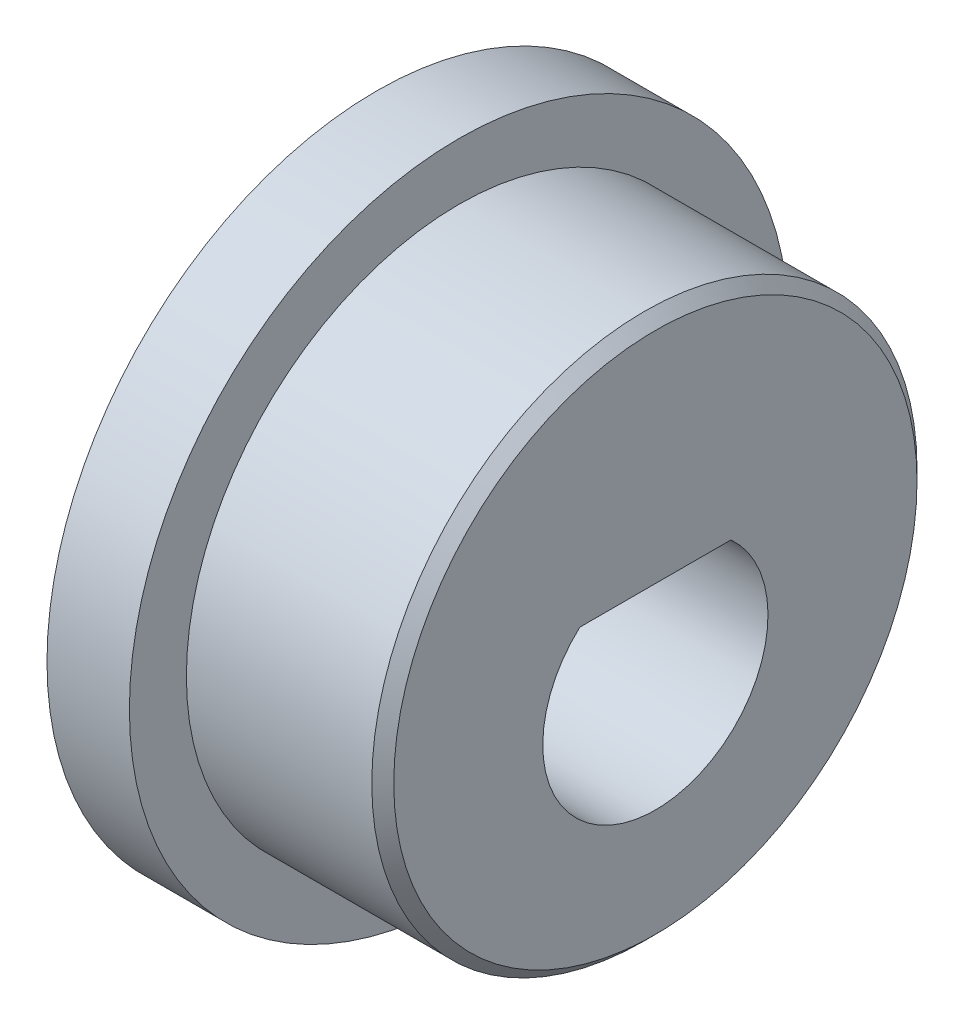
SolidWorks part; units mm, degrees
ref_plane "Ebene vorne" through (0, 0, 0) normal (0, 0, 1) x (1, 0, 0)
ref_plane "Ebene oben" through (0, 0, 0) normal (0, 1, 0) x (1, 0, 0)
ref_plane "Ebene rechts" through (0, 0, 0) normal (1, 0, 0) x (0, 0, -1)
sketch "Skizze1" plane through (0, 0, 0) normal (1, 0, 0) x (0, 0, -1)
  circle A0 centre (0, 1.5) radius 9.925
  dimension "D2" = 19.85
  dimension "D1" = 1.5
extrude "Aufsatz-Linear austragen1" add sketch "Skizze1" along normal blind 7.15
sketch "Skizze2" plane through (0, 0, 0) normal (-1, 0, 0) x (0, 0, 1)
  circle A0 centre (0, 1.5) radius 12
  dimension "D1" = 24
extrude "Aufsatz-Linear austragen2" add sketch "Skizze2" along normal blind 3
sketch "Skizze3" plane through (7.15, 0, 0) normal (1, 0, 0) x (0, 0, -1)
  line L0 (-2.75, 3.041) -> (2.75, 3.041)
  arc A0 (-2.75, 3.041) -> (2.75, 3.041) centre (0, 0) ccw
  dimension "D1" = 4.1
  dimension "D2" = 5.5
extrude "Schnitt-Linear austragen2" cut sketch "Skizze3" against normal through all both and the other way through all
chamfer "Fase1" distance 0.4 angle 45 1 edges at (7.15, 1.5, -9.925)
